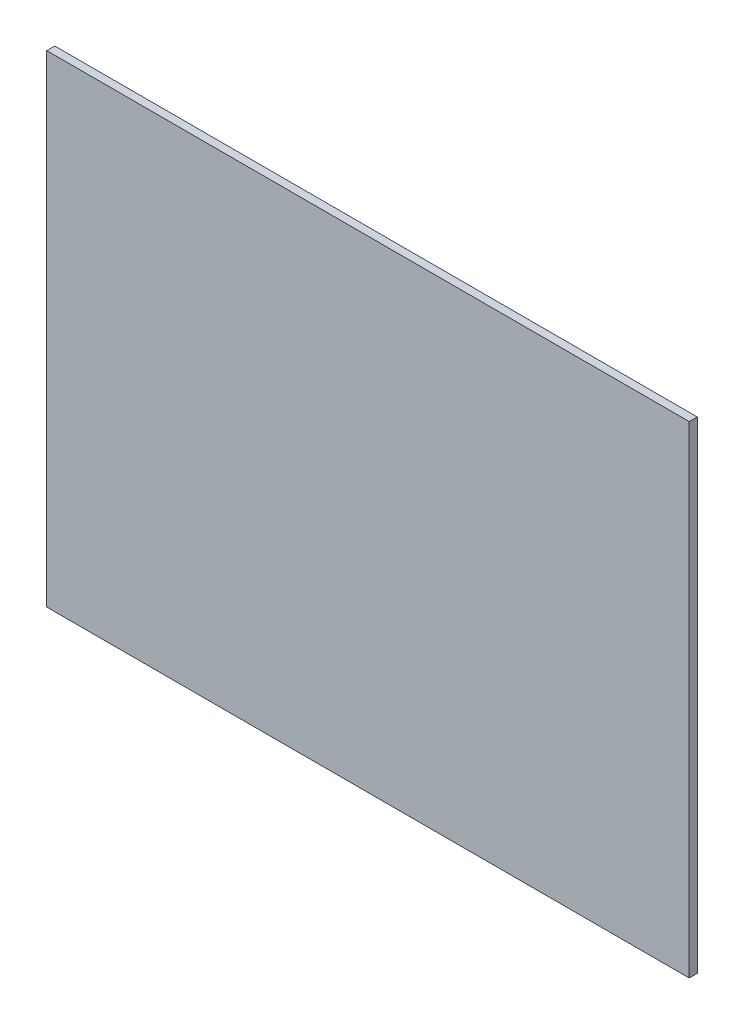
SolidWorks part; units mm, degrees
ref_plane "Front Plane" through (0, 0, 0) normal (0, 0, 1) x (1, 0, 0)
ref_plane "Top Plane" through (0, 0, 0) normal (0, 1, 0) x (1, 0, 0)
ref_plane "Right Plane" through (0, 0, 0) normal (1, 0, 0) x (0, 0, -1)
sketch "Sketch1" plane through (0, 0, 0) normal (0, 0, 1) x (1, 0, 0)
  line L1 (0, 0) -> (800, 0)
  line L2 (0, 0) -> (0, -600)
  line L3 (0, -600) -> (800, -600)
  line L4 (800, 0) -> (800, -600)
  dimension "D1" = 600
  dimension "D2" = 800
extrude "Boss-Extrude1" add sketch "Sketch1" along normal blind 10
